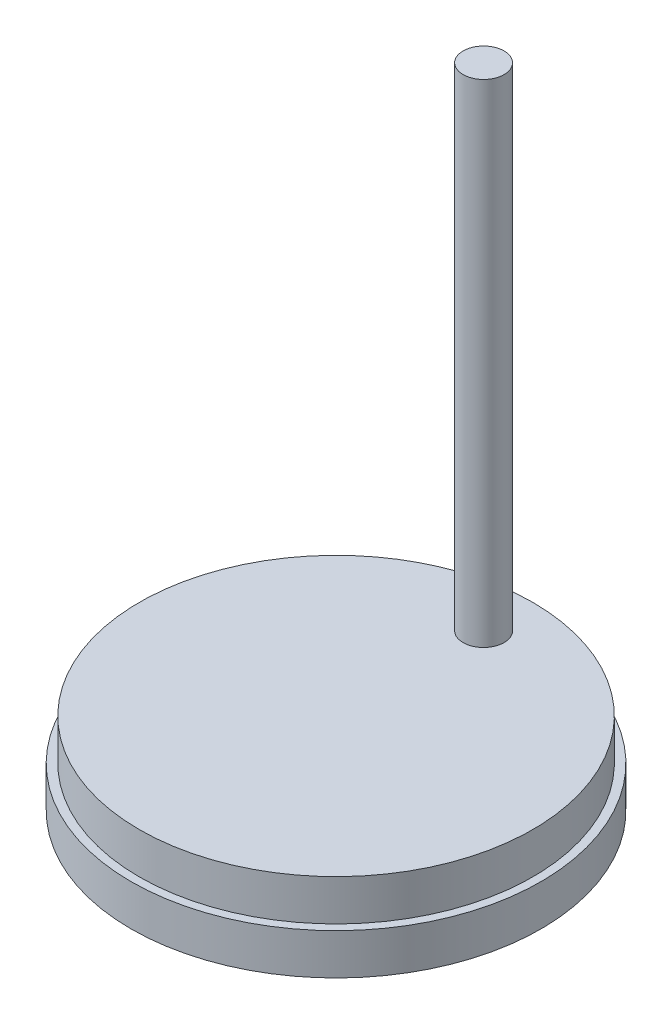
SolidWorks part; units mm, degrees
ref_plane "Front Plane" through (0, 0, 0) normal (0, 0, 1) x (1, 0, 0)
ref_plane "Top Plane" through (0, 0, 0) normal (0, 1, 0) x (1, 0, 0)
ref_plane "Right Plane" through (0, 0, 0) normal (1, 0, 0) x (0, 0, -1)
sketch "Sketch1" plane through (0, 0, 0) normal (0, 1, 0) x (1, 0, 0)
  circle A0 centre (0, 0) radius 50
extrude "Boss-Extrude1" add sketch "Sketch1" along normal blind 10
sketch "Sketch2" plane through (0, 10, 0) normal (0, 1, 0) x (1, 0, 0)
  circle A0 centre (0, 0) radius 48
extrude "Boss-Extrude2" add sketch "Sketch2" along normal blind 10
sketch "Sketch3" plane through (0, 20, 0) normal (0, 1, 0) x (1, 0, 0)
  circle A0 centre (0, 35.9894) radius 5
extrude "Boss-Extrude3" add sketch "Sketch3" along normal blind 120
